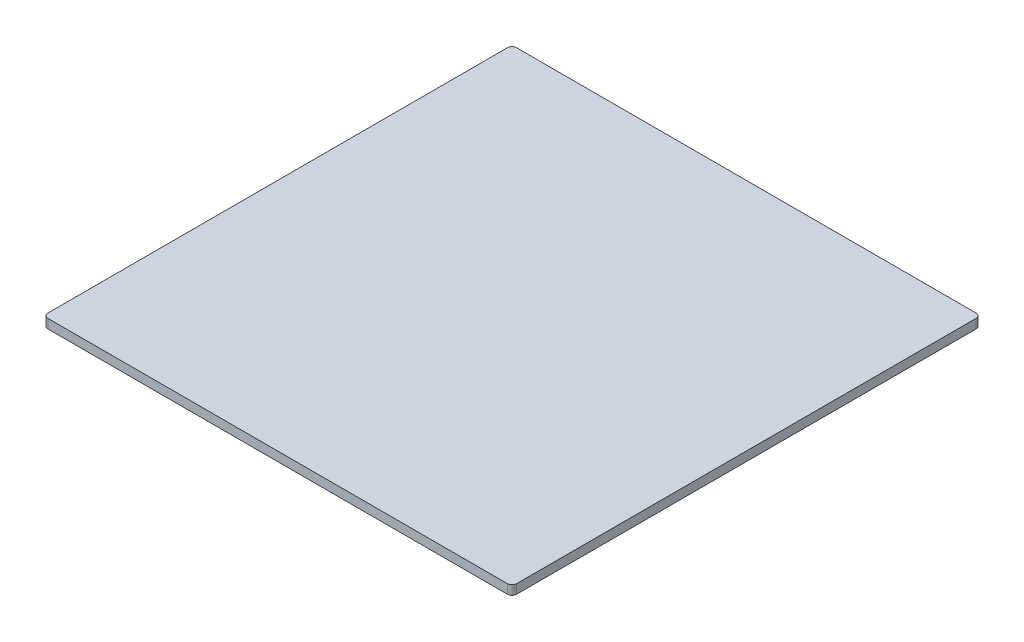
SolidWorks part; units mm, degrees
material "Cobre"
ref_plane "Plano frontal" through (0, 0, 0) normal (0, 0, 1) x (1, 0, 0)
ref_plane "Plano superior" through (0, 0, 0) normal (0, 1, 0) x (1, 0, 0)
ref_plane "Plano direito" through (0, 0, 0) normal (1, 0, 0) x (0, 0, -1)
sketch "Esboço1" plane through (0, 0, 0) normal (0, 1, 0) x (1, 0, 0)
  line L1 (-26.7028, 160.6161) -> (73.2972, 160.6161)
  line L2 (-27.7028, 159.6161) -> (-27.7028, 59.6161)
  line L3 (-26.7028, 58.6161) -> (73.2972, 58.6161)
  line L4 (74.2972, 159.6161) -> (74.2972, 59.6161)
  arc A0 (73.2972, 160.6161) -> (74.2972, 159.6161) centre (73.2972, 159.6161) cw
  arc A1 (73.2972, 58.6161) -> (74.2972, 59.6161) centre (73.2972, 59.6161) ccw
  arc A2 (-27.7028, 59.6161) -> (-26.7028, 58.6161) centre (-26.7028, 59.6161) ccw
  arc A3 (-26.7028, 160.6161) -> (-27.7028, 159.6161) centre (-26.7028, 159.6161) ccw
  dimension "D1" = 1
extrude "Ressalto-extrusão1" add sketch "Esboço1" along normal blind 2
